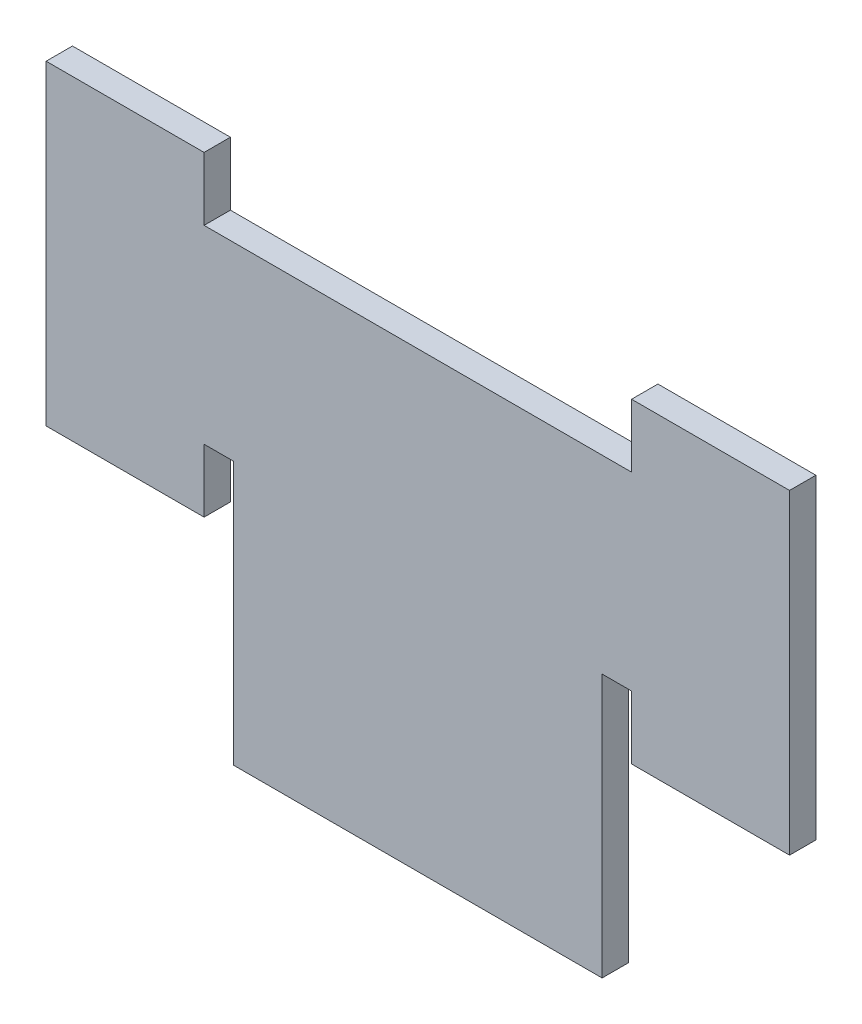
SolidWorks part; units mm, degrees
ref_plane "Front Plane" through (0, 0, 0) normal (0, 0, 1) x (1, 0, 0)
ref_plane "Top Plane" through (0, 0, 0) normal (0, 1, 0) x (1, 0, 0)
ref_plane "Right Plane" through (0, 0, 0) normal (1, 0, 0) x (0, 0, -1)
sketch "Sketch1" plane through (0, 0, 0) normal (0, 0, 1) x (1, 0, 0)
  line L0 (-3.556, 54.61) -> (48.006, 54.61)
  line L1 (-3.556, 31.75) -> (-3.556, 24.13)
  line L2 (0, 31.75) -> (0, 0)
  line L3 (0, 0) -> (44.45, 0)
  line L4 (44.45, 31.75) -> (44.45, 0)
  line L5 (0, 31.75) -> (-3.556, 31.75)
  line L6 (-3.556, 24.13) -> (-22.606, 24.13)
  line L7 (-22.606, 24.13) -> (-22.606, 62.23)
  line L8 (-22.606, 62.23) -> (-3.556, 62.23)
  line L9 (44.45, 31.75) -> (48.006, 31.75)
  line L10 (-3.556, 62.23) -> (-3.556, 54.61)
  line L11 (48.006, 31.75) -> (48.006, 24.13)
  line L12 (48.006, 24.13) -> (67.056, 24.13)
  line L13 (67.056, 24.13) -> (67.056, 62.23)
  line L14 (67.056, 62.23) -> (48.006, 62.23)
  line L15 (48.006, 62.23) -> (48.006, 54.61)
  dimension "D1" = 44.45
  dimension "D2" = 3.556
  dimension "D3" = 3.556
  dimension "D4" = 22.86
  dimension "D5" = 31.75
  dimension "D6" = 38.1
  dimension "D7" = 19.05
extrude "Boss-Extrude1" add sketch "Sketch1" along normal blind 3.175
